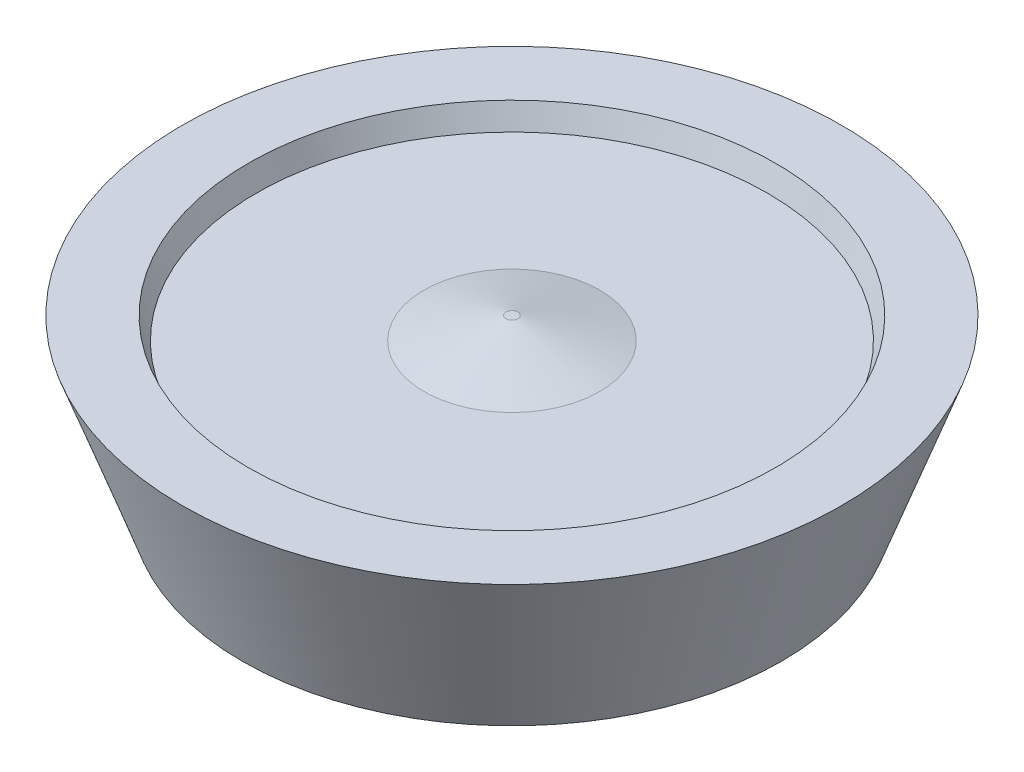
SolidWorks part; units mm, degrees
ref_plane "Front Plane" through (0, 0, 0) normal (0, 0, 1) x (1, 0, 0)
ref_plane "Top Plane" through (0, 0, 0) normal (0, 1, 0) x (1, 0, 0)
ref_plane "Right Plane" through (0, 0, 0) normal (1, 0, 0) x (0, 0, -1)
ref_plane "Plane1" through (0, 0, 0) normal (0, 0, -1) x (-1, 0, 0)
sketch "Sketch1" plane through (0, 0, 0) normal (0, 0, -1) x (-1, 0, 0)
  line L0 (-24.5404, -15) -> (0, -15)
  line L1 (0, -15) -> (0, 0)
  line L2 (0, 0) -> (-0.5359, 0)
  line L3 (-0.5359, 0) -> (-8, -2)
  line L4 (-8, -2) -> (-23.2721, -2)
  line L5 (-23.2721, -2) -> (-24, 0)
  line L6 (-24, 0) -> (-30, 0)
  line L7 (-30, 0) -> (-24.5404, -15)
  line L8 (0, -15) -> (0, 0) construction
revolve "Revolve1" add sketch "Sketch1" angle 360 about L8
